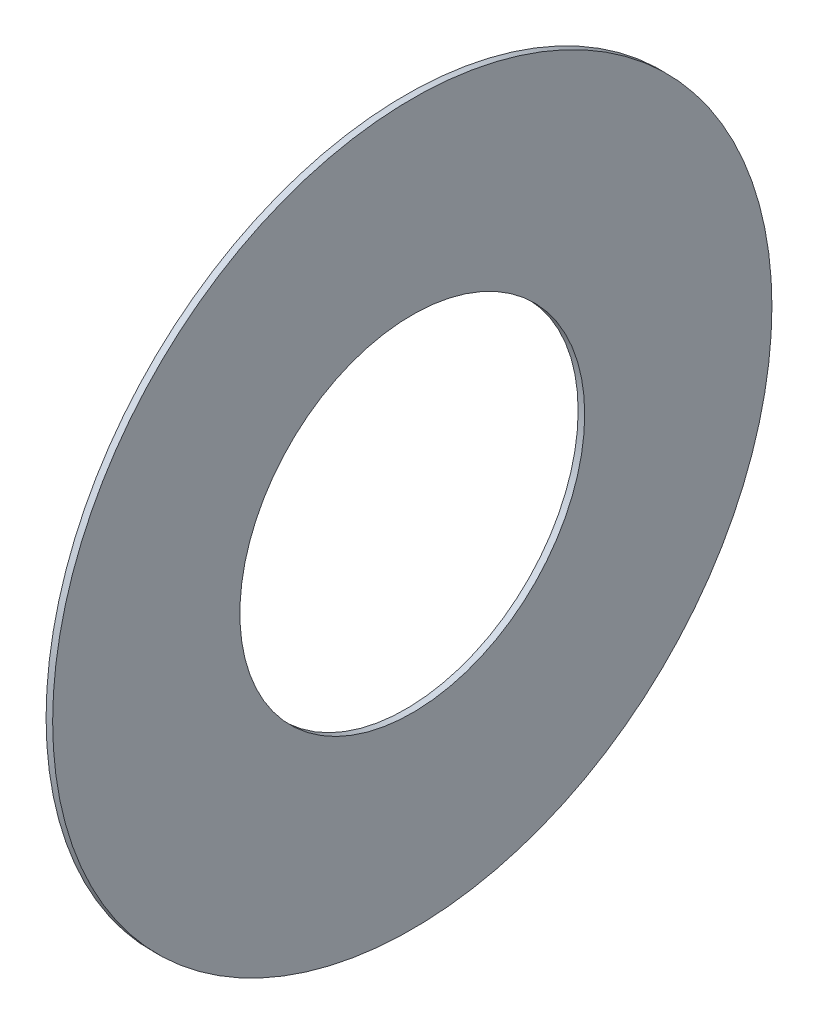
SolidWorks part; units mm, degrees
ref_plane "Plan de face" through (0, 0, 0) normal (0, 0, 1) x (1, 0, 0)
ref_plane "Plan de dessus" through (0, 0, 0) normal (0, 1, 0) x (1, 0, 0)
ref_plane "Plan de droite" through (0, 0, 0) normal (1, 0, 0) x (0, 0, -1)
sketch "Esquisse1" plane through (0, 0, 0) normal (0, 0, 1) x (1, 0, 0)
  line L0 (0, 10.95) -> (-0.2, 10.95)
  line L1 (-0.2, 10.95) -> (-0.2, 5.25)
  line L2 (-0.2, 5.25) -> (0, 5.25)
  line L3 (0, 5.25) -> (0, 10.95)
  line L4 (-0.2, 0) -> (0, 0) construction
revolve "Révolution1" add sketch "Esquisse1" angle 360 about L4
